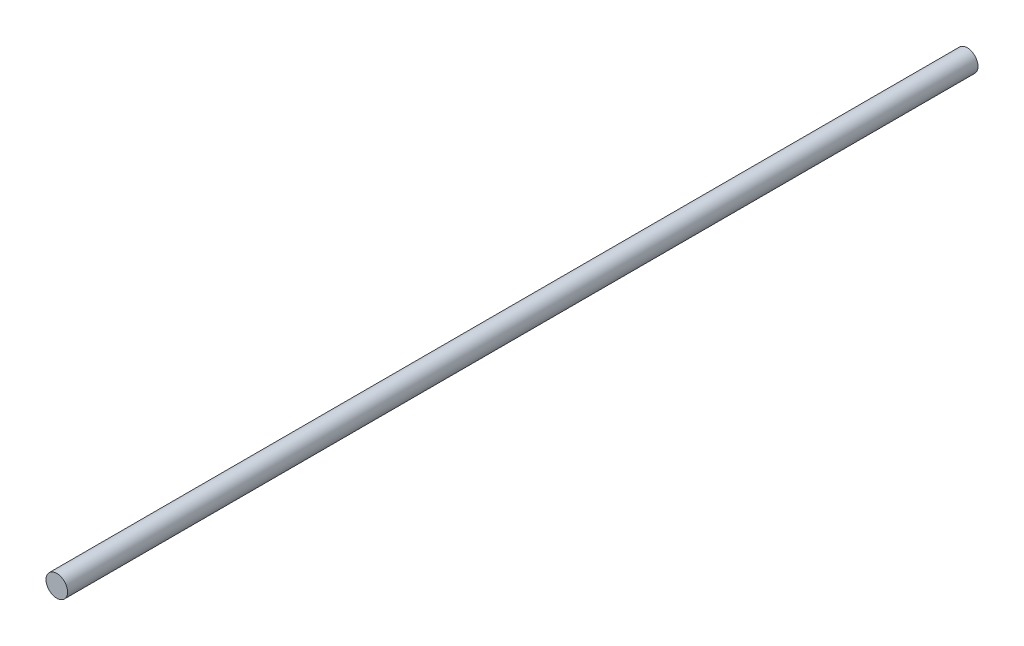
SolidWorks part; units mm, degrees
ref_plane "Front Plane" through (0, 0, 0) normal (0, 0, 1) x (1, 0, 0)
ref_plane "Top Plane" through (0, 0, 0) normal (0, 1, 0) x (1, 0, 0)
ref_plane "Right Plane" through (0, 0, 0) normal (1, 0, 0) x (0, 0, -1)
sketch "Sketch1" plane through (0, 0, 0) normal (0, 0, 1) x (1, 0, 0)
  circle A0 centre (0, 0) radius 6.35
extrude "Boss-Extrude1" add sketch "Sketch1" along normal mid plane 536
cosmetic thread "Cosmetic Thread1" parameters "D1"=44.5, "D2"=11.1887
cosmetic thread "Cosmetic Thread2" parameters "D1"=44.5, "D2"=11.1887
cosmetic thread "Cosmetic Thread3" parameters "D1"=44.5, "D2"=11.1887
